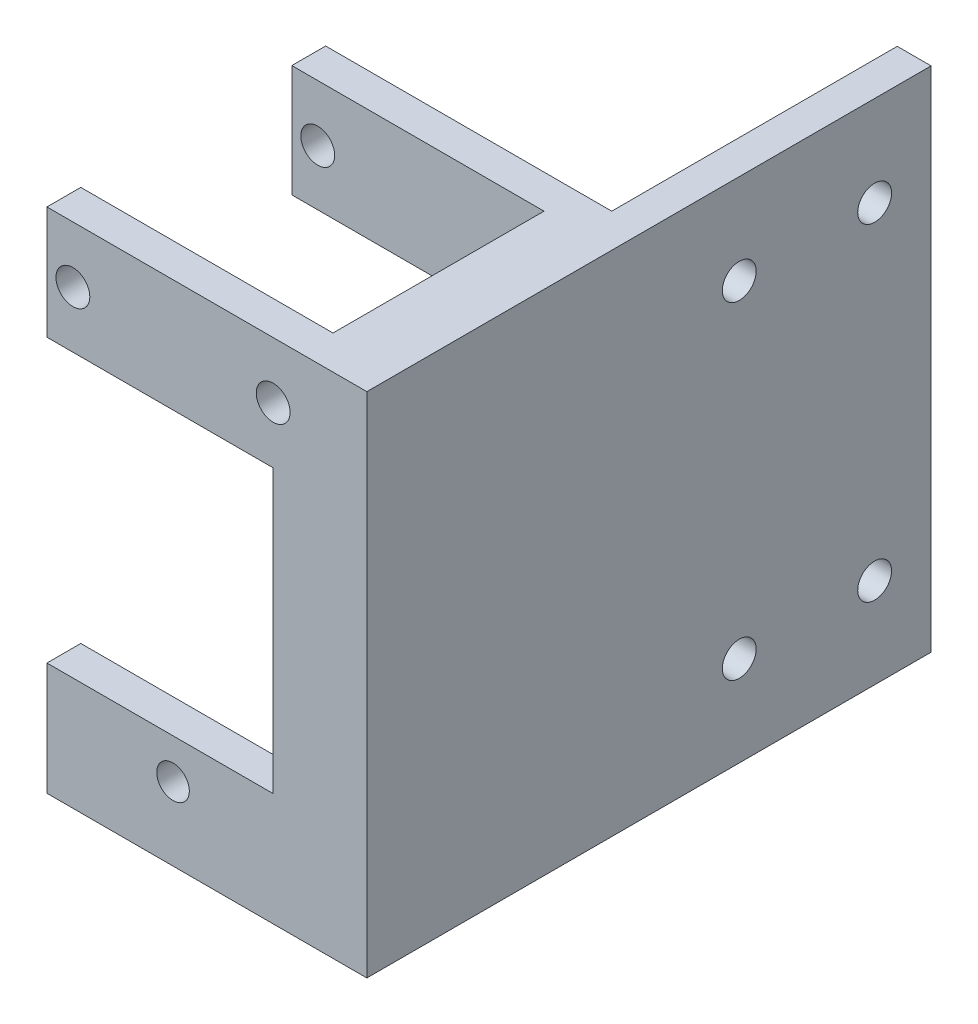
SolidWorks part; units mm, degrees
ref_plane "Front Plane" through (0, 0, 0) normal (0, 0, 1) x (1, 0, 0)
ref_plane "Top Plane" through (0, 0, 0) normal (0, 1, 0) x (1, 0, 0)
ref_plane "Right Plane" through (0, 0, 0) normal (1, 0, 0) x (0, 0, -1)
sketch "Sketch2" plane through (0, 0, 0) normal (0, 0, 1) x (1, 0, 0)
  line L1 (12.675, -22.5) -> (-12.675, -22.5)
  line L2 (12.675, -22.5) -> (12.675, 22.5)
  line L3 (12.675, 22.5) -> (-12.675, 22.5)
  line L4 (-12.675, -22.5) -> (-12.675, 22.5)
  line L5 (12.675, -22.5) -> (-12.675, 22.5) construction
  line L6 (12.675, 22.5) -> (-12.675, -22.5) construction
  line L7 (-12.675, 22.5) -> (12.675, 22.5)
  line L8 (-12.675, 22.5) -> (-12.675, 12.5)
  line L9 (-12.675, 12.5) -> (12.675, 12.5)
  line L10 (12.675, 22.5) -> (12.675, 12.5)
  line L11 (-12.675, -22.5) -> (12.675, -22.5)
  line L12 (-12.675, -22.5) -> (-12.675, -12.5)
  line L13 (-12.675, -12.5) -> (12.675, -12.5)
  line L14 (12.675, -22.5) -> (12.675, -12.5)
  line L15 (12.675, 12.5) -> (7.375, 12.5)
  line L16 (12.675, 12.5) -> (12.675, -12.5)
  line L17 (12.675, -12.5) -> (7.375, -12.5)
  line L18 (7.375, 12.5) -> (7.375, -12.5)
  line L19 (-12.675, 12.5) -> (7.375, 12.5)
  line L20 (-12.675, 12.5) -> (-12.675, -12.5)
  line L21 (-12.675, -12.5) -> (7.375, -12.5)
  line L22 (7.375, 12.5) -> (7.375, -12.5)
  circle A5 centre (-10.375, 17.5) radius 1.5
  circle A6 centre (7.375, 17.5) radius 1.5
  circle A8 centre (-1.5, -16.025) radius 1.445
  point P0 (0, 0)
  dimension "D5" = 5
  dimension "D6" = 2.89
  dimension "D7" = 20.05
  dimension "D8" = 2.3
  dimension "D9" = 3
  dimension "D10" = 6.475
  dimension "D11" = 14.175
  dimension "D17" = 5
  dimension "D18" = 17.75
  dimension "D19" = 3
  dimension "D1" = 25.35
  dimension "D2" = 45
  dimension "D3" = 10
  dimension "D4" = 10
extrude "Boss-Extrude1" add sketch "Sketch2" against normal blind 3
sketch "Sketch3" plane through (12.675, 0, 0) normal (1, 0, 0) x (0, 0, -1)
  line L1 (0, 22.5) -> (50, 22.5)
  line L2 (0, 22.5) -> (0, -22.5)
  line L3 (0, -22.5) -> (50, -22.5)
  line L4 (50, 22.5) -> (50, -22.5)
  dimension "D1" = 50
  dimension "D2" = 45
extrude "Boss-Extrude2" add sketch "Sketch3" along normal blind 3
sketch "Sketch7" plane through (0, 22.5, 0) normal (0, 1, 0) x (1, 0, 0)
  line L0 (15.675, 50) -> (15.675, 0) construction
  line L1 (15.675, 24.7) -> (-22.675, 24.7)
  line L2 (15.675, 24.7) -> (15.675, 21.7)
  line L3 (15.675, 21.7) -> (-22.675, 21.7)
  line L4 (-22.675, 24.7) -> (-22.675, 21.7)
  line L5 (12.675, 3) -> (-12.675, 3) construction
  dimension "D1" = 18.7
  dimension "D2" = 3
  dimension "D3" = 38.35
extrude "Boss-Extrude3" add sketch "Sketch7" against normal blind 45
sketch "Sketch8" plane through (0, 0, -21.7) normal (0, 0, 1) x (1, 0, 0)
  line L0 (15.675, 22.5) -> (15.675, -22.5) construction
  line L1 (-12.675, 22.5) -> (15.675, 22.5)
  line L2 (-12.675, 22.5) -> (-12.675, 12.5728)
  line L3 (-12.675, 12.5728) -> (15.675, 12.5728)
  line L4 (15.675, 22.5) -> (15.675, 12.5728)
  line L6 (-12.675, -12.5) -> (15.675, -12.5)
  line L7 (-12.675, -12.5) -> (-12.675, -22.5)
  line L8 (-12.675, -22.5) -> (15.675, -22.5)
  line L9 (15.675, -12.5) -> (15.675, -22.5)
  line L10 (7.375, -12.5) -> (15.675, -12.5)
  line L11 (7.375, -12.5) -> (7.375, 12.5728)
  line L12 (7.375, 12.5728) -> (15.675, 12.5728)
  line L13 (15.675, -12.5) -> (15.675, 12.5728)
  line M3 (-22.675, 22.5) -> (-22.675, -22.5)
extrude "Cut-Extrude1" cut sketch "Sketch8" against normal blind 5 contours L6 L11 L3 M3
sketch "Sketch14" plane through (0, 0, -21.7) normal (0, 0, 1) x (1, 0, 0)
  circle A0 centre (-10.375, 17.5) radius 1.5
  circle A1 centre (7.375, 17.5) radius 1.5
  circle A5 centre (-1.5, -16.025) radius 1.45
  dimension "D1" = 2.9
  dimension "D2" = 33.525
  dimension "D4" = 3
  dimension "D5" = 3
extrude "Cut-Extrude5" cut sketch "Sketch14" against normal blind 5
sketch "Sketch15" plane through (12.675, 0, 0) normal (-1, 0, 0) x (0, 0, 1)
  line L0 (-50, -22.5) -> (-50, 22.5) construction
  line L1 (-50, 22.5) -> (-24.7, 22.5) construction
  line L2 (-24.7, -22.5) -> (-50, -22.5) construction
  circle A0 centre (-33, 14.5) radius 1.5
  circle A1 centre (-33, -14.5) radius 1.5
  circle A2 centre (-45, 14.5) radius 1.5
  circle A3 centre (-45, -14.5) radius 1.5
  dimension "D1" = 5
  dimension "D2" = 5
  dimension "D3" = 12
  dimension "D4" = 12
  dimension "D5" = 8
  dimension "D6" = 8
  dimension "D7" = 8
  dimension "D8" = 8
  dimension "D9" = 3
  dimension "D10" = 3
  dimension "D11" = 3
  dimension "D12" = 3
extrude "Cut-Extrude6" cut sketch "Sketch15" against normal blind 5
sketch "Sketch11" plane through (15.675, 0, 0) normal (1, 0, 0) x (0, 0, -1)
  line L0 (0, -22.5) -> (50, -22.5) construction
  line L8 (50, -22.5) -> (50, 22.5) construction
  line L11 (50, 22.5) -> (0, 22.5) construction
  circle A4 centre (33, 14.5) radius 1.5
  circle A5 centre (45, 14.5) radius 1.5
  circle A6 centre (33, -12.5) radius 1.5
  circle A7 centre (45, -12.5) radius 1.5
  dimension "D2" = 5
  dimension "D3" = 8
  dimension "D4" = 27
  dimension "D5" = 5
  dimension "D7" = 3
  dimension "D6" = 8
  dimension "D8" = 3
  dimension "D9" = 3
  dimension "D10" = 3
  dimension "D11" = 12
  dimension "D12" = 12
  dimension "D13" = 10
sketch "Sketch12" plane through (12.675, 0, 0) normal (-1, 0, 0) x (0, 0, 1)
  line L1 (-21.7, 22.5) -> (-3, 22.5)
  line L2 (-21.7, 22.5) -> (-21.7, -22.5)
  line L3 (-21.7, -22.5) -> (-3, -22.5)
  line L4 (-3, 22.5) -> (-3, -22.5)
extrude "Boss-Extrude4" add sketch "Sketch12" along normal blind 3
